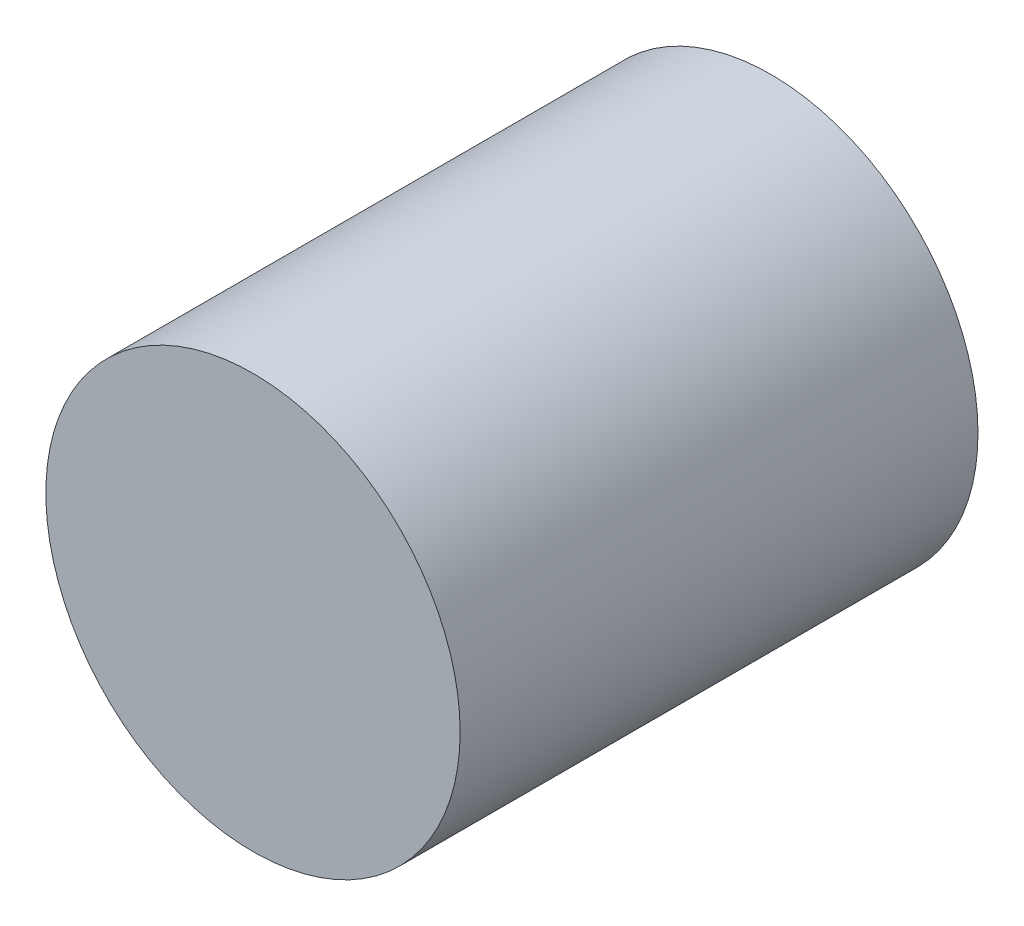
SolidWorks part; units mm, degrees
ref_plane "前基準面" through (0, 0, 0) normal (0, 0, 1) x (1, 0, 0)
ref_plane "上基準面" through (0, 0, 0) normal (0, 1, 0) x (1, 0, 0)
ref_plane "右基準面" through (0, 0, 0) normal (1, 0, 0) x (0, 0, -1)
sketch "草圖1" plane through (0, 0, 0) normal (0, 0, 1) x (1, 0, 0)
  circle A0 centre (0, 0) radius 2
  dimension "D1" = 4
extrude "填料-伸長1" add sketch "草圖1" along normal mid plane 5
